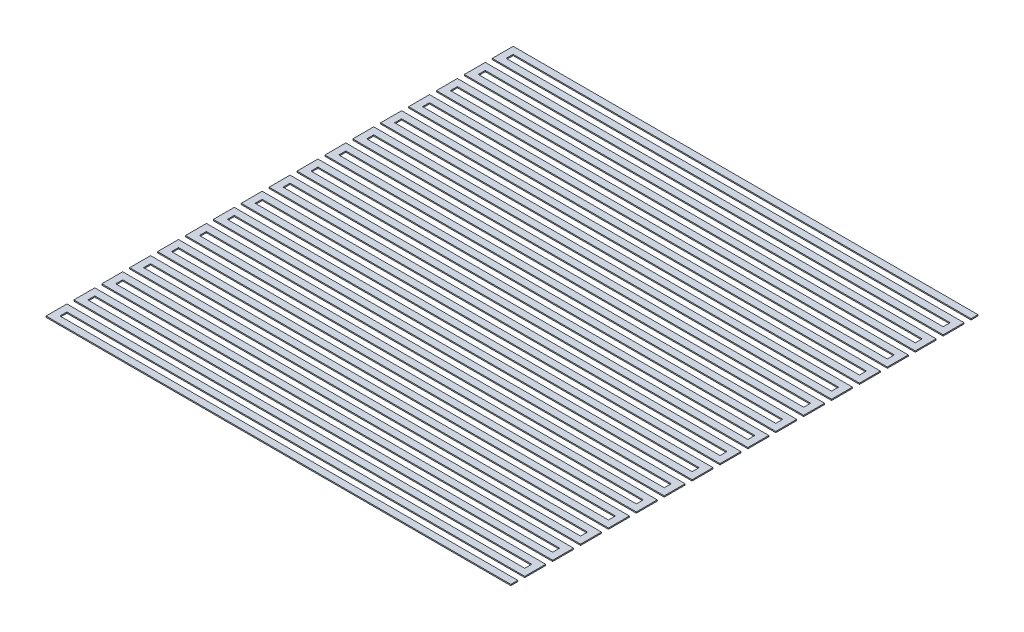
SolidWorks part; units mm, degrees
ref_plane "Front Plane" through (0, 0, 0) normal (0, 0, 1) x (1, 0, 0)
ref_plane "Top Plane" through (0, 0, 0) normal (0, 1, 0) x (1, 0, 0)
ref_plane "Right Plane" through (0, 0, 0) normal (1, 0, 0) x (0, 0, -1)
sketch "Base Guidlines" plane through (0, 0, 0) normal (0, 1, 0) x (1, 0, 0)
  line L0 (-4.5961, 9.2) -> (-4.5961, 8.5)
  line L1 (-10, -10) -> (10, -10)
  line L2 (-10, -10) -> (-10, 10)
  line L3 (-10, 10) -> (10, 10)
  line L4 (10, -10) -> (10, 10)
  line L5 (-10, -10) -> (10, 10) construction
  line L6 (-10, 10) -> (10, -10) construction
  line L7 (-10, 10) -> (10, 10)
  line L8 (-10, 10) -> (-10, 9.2)
  line L9 (-10, 9.2) -> (10, 9.2)
  line L10 (10, 10) -> (10, 9.2)
  line L11 (-4.5961, -9.2) -> (-4.5961, -8.5)
  line L12 (-10, -10) -> (10, -10)
  line L13 (-10, -10) -> (-10, -9.2)
  line L14 (-10, -9.2) -> (10, -9.2)
  line L15 (10, -10) -> (10, -9.2)
  line L17 (-10, -9.2) -> (10, -9.2)
  line L18 (-10, -9.2) -> (-10, -8.5)
  line L19 (-10, -8.5) -> (10, -8.5)
  line L20 (10, -9.2) -> (10, -8.5)
  line L21 (-10, 9.2) -> (10, 9.2)
  line L22 (-10, 9.2) -> (-10, 8.5)
  line L23 (-10, 8.5) -> (10, 8.5)
  line L24 (10, 9.2) -> (10, 8.5)
  point P0 (0, 0)
  dimension "D1" = 20
  dimension "D2" = 20
  dimension "D3" = 0.7
  dimension "D4" = 0.7
sketch "Mirror axis x" plane through (0, 0, 0) normal (0, 1, 0) x (1, 0, 0)
  line L0 (-10, 0) -> (10, 0)
  line L1 (-10, -10) -> (-10, 10) construction
  line L2 (10, -10) -> (10, 10) construction
sketch "TopBlock" plane through (0, 0, 0) normal (0, 1, 0) x (1, 0, 0)
  line L0 (-10, 10) -> (10, -10) construction
  line L1 (-10, 10) -> (-9.7, 10)
  line L2 (-10, 10) -> (-10, 9.7)
  line L3 (-10, 9.7) -> (-10, 9.4)
  line L4 (-9.7, 10) -> (10, 10)
  line L5 (-9.7, 9.4) -> (10, 9.4)
  line L6 (-10, 9.4) -> (-10, 9.1)
  line L7 (-10, 9.1) -> (10, 9.1)
  line L8 (-9.7, 9.4) -> (-9.7, 9.7)
  line L9 (10, 9.4) -> (10, 9.1)
  line L11 (-9.7, 9.7) -> (10, 9.7)
  line L12 (10, 9.7) -> (10, 10)
  dimension "D1" = 0.3
  dimension "D2" = 0.3
  dimension "D3" = 0.3
extrude "Extruded object" add sketch "TopBlock" along normal blind 0.05
sketch "Mirror axis y" plane through (0, 0, 0) normal (0, 1, 0) x (1, 0, 0)
  line L0 (0, 10) -> (0, -10)
  line L3 (10, 10) -> (-10, 10) construction
  dimension "D1" = 20
sketch "Sketch2" plane through (0, 0, 0) normal (0, 1, 0) x (1, 0, 0)
  line L0 (10, 9.1) -> (10, 8.8)
  line L1 (10, 8.8) -> (10, 8.5)
  line L2 (9.7, 9.1) -> (9.7, 8.8)
  line L3 (-10, 9.1) -> (10, 9.1) construction
  line L4 (-10, 8.8) -> (-10, 8.5)
  line L5 (9.7, 8.8) -> (-10, 8.8)
  line L6 (10, 8.5) -> (-9.7, 8.5)
  line L7 (-10, 8.5) -> (-10, 8.2)
  line L8 (-9.7, 8.5) -> (-9.7, 8.2)
  line L9 (-10, 8.2) -> (-10, 7.9)
  line L10 (-10, 7.9) -> (10, 7.9)
  line L11 (10, 7.9) -> (10, 8.2)
  line L12 (10, 8.2) -> (-9.7, 8.2)
  line L21 (-10, 10) -> (-10, 9.1)
  line L22 (-10, 9.1) -> (10, 9.1)
  line L23 (10, 9.1) -> (10, 9.4)
  line L24 (10, 9.4) -> (-9.7, 9.4)
  line L25 (-9.7, 9.4) -> (-9.7, 9.7)
  line L26 (-9.7, 9.7) -> (10, 9.7)
  line L27 (10, 9.7) -> (10, 10)
  line L28 (10, 10) -> (-10, 10)
  line L30 (9.7, 9.1) -> (10, 9.1)
  dimension "D1" = 0.3
  dimension "D2" = 0.3
  dimension "D3" = 0.3
  dimension "D4" = 0.3
  dimension "D5" = 0.3
  dimension "D6" = 0
extrude "Boss-Extrude1" add sketch "Sketch2" along normal blind 0.05
pattern_linear "LPattern1" count 16 spacing 1.2 along (0, 0, 1) of "Boss-Extrude1"
